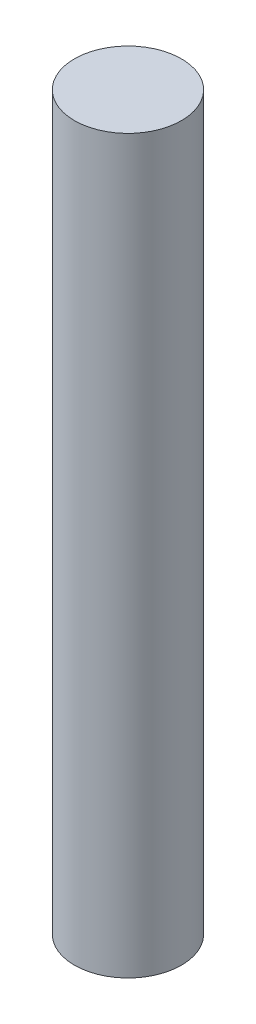
SolidWorks part; units mm, degrees
ref_plane "Front Plane" through (0, 0, 0) normal (0, 0, 1) x (1, 0, 0)
ref_plane "Top Plane" through (0, 0, 0) normal (0, 1, 0) x (1, 0, 0)
ref_plane "Right Plane" through (0, 0, 0) normal (1, 0, 0) x (0, 0, -1)
sketch "Sketch1" plane through (0, 0, 0) normal (0, 1, 0) x (1, 0, 0)
  circle A0 centre (0, 0) radius 3
  dimension "D1" = 6
extrude "Boss-Extrude1" add sketch "Sketch1" along normal blind 41
